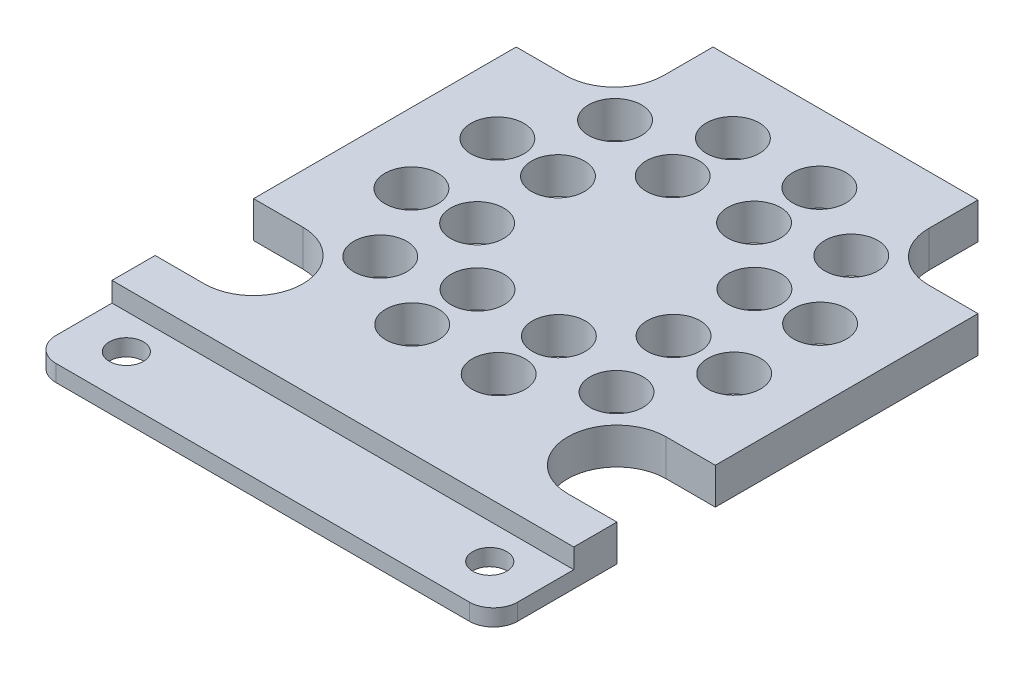
SolidWorks part; units mm, degrees
ref_plane "Front Plane" through (0, 0, 0) normal (0, 0, 1) x (1, 0, 0)
ref_plane "Top Plane" through (0, 0, 0) normal (0, 1, 0) x (1, 0, 0)
ref_plane "Right Plane" through (0, 0, 0) normal (1, 0, 0) x (0, 0, -1)
sketch "Sketch1" plane through (0, 0, 0) normal (0, 1, 0) x (1, 0, 0)
  line L0 (15.25, -7.85) -> (12, -7.85) construction
  line L1 (-15.25, 19.25) -> (15.25, 19.25) construction
  line L2 (-15.25, 19.25) -> (-15.25, -19.25) construction
  line L3 (-15.25, -19.25) -> (15.25, -19.25) construction
  line L4 (15.25, 19.25) -> (15.25, -19.25) construction
  line L5 (-15.25, 19.25) -> (15.25, -19.25) construction
  line L6 (-15.25, -19.25) -> (15.25, 19.25) construction
  line L7 (12, -7.85) -> (12, -19.25) construction
  line L8 (12, 19.25) -> (12, 16) construction
  line L9 (12, 16) -> (15.25, 16) construction
  line L10 (-12, 19.25) -> (-12, 16) construction
  line L11 (-12, 16) -> (-15.25, 16) construction
  line L12 (-15.25, -7.85) -> (-12, -7.85) construction
  line L13 (-12, -7.85) -> (-12, -19.25) construction
  line L14 (-8.75, 16) -> (-8.75, 19.25)
  line L15 (-12, 12.75) -> (-15.25, 12.75)
  line L16 (-12, -4.6) -> (-15.25, -4.6)
  line L17 (-12, -11.1) -> (-15.25, -11.1)
  line L18 (12, -11.1) -> (15.25, -11.1)
  line L19 (12, -4.6) -> (15.25, -4.6)
  line L20 (12, 12.75) -> (15.25, 12.75)
  line L21 (8.75, 16) -> (8.75, 19.25)
  line L22 (8.75, 19.25) -> (-8.75, 19.25)
  line L23 (15.25, 12.75) -> (15.25, -4.6)
  line L24 (-15.25, 12.75) -> (-15.25, -4.6)
  line L25 (-15.25, -11.1) -> (-15.25, -19.25)
  line L26 (-15.25, -19.25) -> (15.25, -19.25)
  line L27 (15.25, -19.25) -> (15.25, -11.1)
  line L28 (-12, -7.85) -> (-8.75, -7.85) construction
  circle A0 centre (-12, 16) radius 2.55 construction
  circle A1 centre (12, 16) radius 2.55 construction
  circle A2 centre (12, -7.85) radius 2.55 construction
  circle A3 centre (-12, -7.85) radius 2.55 construction
  arc A4 (-12, 12.75) -> (-8.75, 16) centre (-12, 16) ccw
  arc A5 (8.75, 16) -> (12, 12.75) centre (12, 16) ccw
  arc A6 (-12, -11.1) -> (-12, -4.6) centre (-12, -7.85) ccw
  arc A7 (12, -4.6) -> (12, -11.1) centre (12, -7.85) ccw
  point P0 (0, 0)
  dimension "D4" = 5.1
  dimension "D1" = 30.5
  dimension "D2" = 38.5
  dimension "D3" = 3.25
  dimension "D5" = 11.4
extrude "Boss-Extrude1" add sketch "Sketch1" along normal blind 2.4
sketch "Sketch2" plane through (0, 0, -19.25) normal (0, 0, -1) x (-1, 0, 0)
  line L0 (0, 0) -> (5.75, 0)
  line L1 (-8.75, 0) -> (8.75, 0) construction
  line L2 (5.75, 0) -> (5.75, -1.6)
  line L3 (5.75, -1.6) -> (-5.75, -1.6)
  line L4 (-5.75, -1.6) -> (-5.75, 0)
  line L5 (-5.75, 0) -> (0, 0)
  dimension "D1" = 11.5
  dimension "D2" = 1.6
extrude "Boss-Extrude2" add sketch "Sketch2" along normal blind 2.2 and the other way blind 2.2
sketch "Sketch3" plane through (0, 2.4, 0) normal (0, 1, 0) x (1, 0, 0)
  line L0 (-15.25, -19.25) -> (15.25, -19.25) construction
  line L1 (-15.25, -11.1) -> (-15.25, -19.25) construction
  line L2 (15.25, -19.25) -> (15.25, -11.1) construction
  circle A0 centre (-12, -16.25) radius 1.125
  circle A1 centre (12, -16.25) radius 1.125
  dimension "D5" = 2.25
  dimension "D6" = 2.25
  dimension "D1" = 3
  dimension "D2" = 3
  dimension "D3" = 3.25
  dimension "D4" = 3.25
extrude "Cut-Extrude1" cut sketch "Sketch3" against normal through all
sketch "Sketch4" plane through (-15.25, 0, 0) normal (-1, 0, 0) x (0, 0, 1)
  line L0 (19.25, 1.1) -> (13.95, 1.1)
  line L1 (19.25, 2.4) -> (19.25, 0) construction
  line L2 (13.95, 1.1) -> (13.95, 2.4)
  line L3 (11.1, 2.4) -> (19.25, 2.4) construction
  line L4 (13.95, 2.4) -> (19.25, 2.4)
  line L5 (19.25, 2.4) -> (19.25, 1.1)
  line L6 (11.1, 0) -> (19.25, 0) construction
  dimension "D1" = 1.1
  dimension "D2" = 5.3
extrude "Cut-Extrude2" cut sketch "Sketch4" against normal through all
fillet "Fillet1" radius 1.6 2 edges at (15.25, 0.55, 19.25) (-15.25, 0.55, 19.25)
fillet "Fillet2" radius 0.25 1 edges at (0, 0, -19.25)
fillet "Fillet3" radius 1 1 edges at (0, 0, -17.05)
sketch "Sketch5" plane through (0, 2.4, 0) normal (0, 1, 0) x (1, 0, 0)
  line L0 (-12, 16) -> (12, -7.85) construction
  line L1 (12, 16) -> (-12, -7.85) construction
  line L2 (0, 4.075) -> (-10.1758, 8.2526)
  circle A0 centre (-7.8025, 11.8288) radius 1.75
  circle A1 centre (0, 4.075) radius 11 construction
  circle A9 centre (-6.4755, 6.7335) radius 1.75
  circle A10 centre (-6.4587, 1.376) radius 1.75
  circle A11 centre (-2.6585, -2.4005) radius 1.75
  circle A12 centre (2.699, -2.3837) radius 1.75
  circle A13 centre (6.4755, 1.4165) radius 1.75
  circle A14 centre (6.4587, 6.774) radius 1.75
  circle A15 centre (2.6585, 10.5505) radius 1.75
  circle A16 centre (-2.699, 10.5337) radius 1.75
  circle A17 centre (-2.8803, 14.6912) radius 1.75
  circle A18 centre (2.8137, 14.7091) radius 1.75
  circle A19 centre (7.7538, 11.8775) radius 1.75
  circle A20 centre (10.6162, 6.9553) radius 1.75
  circle A21 centre (10.6341, 1.2613) radius 1.75
  circle A22 centre (7.8025, -3.6788) radius 1.75
  circle A23 centre (2.8803, -6.5412) radius 1.75
  circle A24 centre (-2.8137, -6.5591) radius 1.75
  circle A25 centre (-7.7538, -3.7275) radius 1.75
  circle A26 centre (-10.6162, 1.1947) radius 1.75
  circle A27 centre (-10.6341, 6.8887) radius 1.75
  point P10 (0, 4.075)
  dimension "D1" = 3.5
  dimension "D2" = 11
  dimension "D4" = 7
  dimension "D5" = 22.5
  dimension "D6" = 8
  dimension "D3" = 12
extrude "Cut-Extrude3" cut sketch "Sketch5" against normal through all
